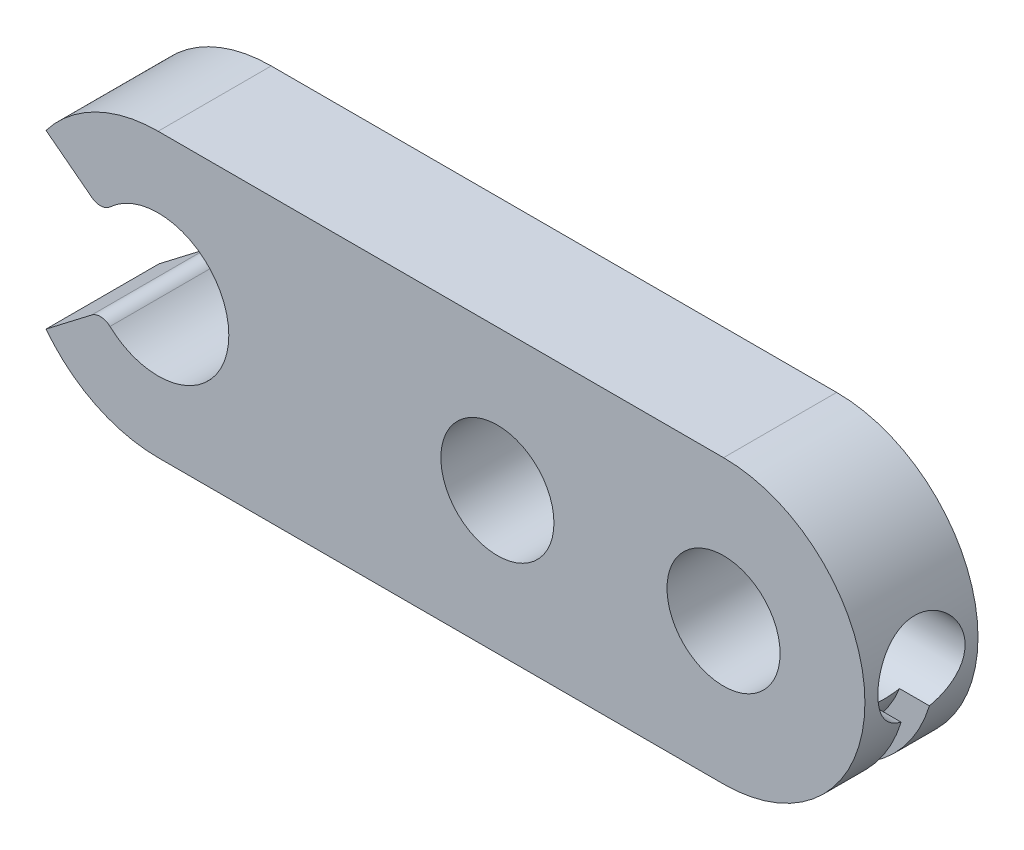
SolidWorks part; units mm, degrees
ref_plane "Front Plane" through (0, 0, 0) normal (0, 0, 1) x (1, 0, 0)
ref_plane "Top Plane" through (0, 0, 0) normal (0, 1, 0) x (1, 0, 0)
ref_plane "Right Plane" through (0, 0, 0) normal (1, 0, 0) x (0, 0, -1)
sketch "Sketch1" plane through (0, 0, 0) normal (0, 0, 1) x (1, 0, 0)
  line L0 (-3.9668, 3.0438) -> (-1.9834, 1.5219)
  line L1 (-1.9834, -1.5219) -> (-3.9668, -3.0438)
  line L2 (0, 5) -> (20, 5)
  line L3 (20, -5) -> (0, -5)
  arc A0 (-3.9668, 3.0438) -> (0, 5) centre (0, 0) cw
  arc A1 (-1.9834, 1.5219) -> (-1.9834, -1.5219) centre (0, 0) cw
  arc A2 (20, 5) -> (20, -5) centre (20, 0) cw
  arc A3 (0, -5) -> (-3.9668, -3.0438) centre (0, 0) cw
  dimension "D2" = 2.5
  dimension "D3" = 5
  dimension "D4" = 20
  dimension "D1" = 75
extrude "Boss-Extrude1" add sketch "Sketch1" along normal blind 4
fillet "Fillet1" radius 0.5 2 edges at (-1.9834, 1.5219, 2) (-1.9834, -1.5219, 2)
sketch "Sketch2" plane through (0, 0, 4) normal (0, 0, 1) x (1, 0, 0)
  circle A0 centre (20, 0) radius 2
  arc A1 (20, -5) -> (20, 5) centre (20, 0) ccw construction
  arc A2 (20, -5) -> (20, 5) centre (20, 0) ccw construction
  point P2 (20.0011, 2.2705)
  point P7 (15.4313, 0)
  point P8 (19.7712, 0)
  dimension "D1" = 4
extrude "Cut-Extrude1" cut sketch "Sketch2" against normal blind 10
sketch "Sketch3" plane through (0, 0, 4) normal (0, 0, 1) x (1, 0, 0)
  circle A2 centre (12, 0) radius 2
  point P2 (11.7761, 2.3074)
  point P3 (0, 0)
  dimension "D1" = 4
  dimension "D2" = 12
extrude "Cut-Extrude2" cut sketch "Sketch3" against normal up to vertex (4 mm away) up to point (0, 0, 0)
sketch "Sketch4" plane through (0, 0, 0) normal (1, 0, 0) x (0, 0, -1)
  line L0 (-2, 0) -> (-2, 5) construction
  line L1 (-4, 5) -> (0, 5) construction
  circle A0 centre (-2, 0) radius 1.5437
  dimension "D1" = 3.0875
extrude "Cut-Extrude3" cut sketch "Sketch4" against normal blind 30 from offset 50
sketch "Sketch5" plane through (0, 0, 0) normal (0, 0, -1) x (-1, 0, 0)
  line L19 (-24, 0) -> (-25, 0)
  line L20 (0, -4) -> (-20, -4)
  line L21 (3, -4) -> (-20, -4)
  line L23 (0, -5) -> (-20, -5)
  line L24 (0, -5) -> (-20, -5) construction
  line L25 (0, -5) -> (3, -5)
  line L30 (3, -5) -> (3, -4)
  arc A25 (-20, 5) -> (-20, -5) centre (-20, 0) ccw construction
  arc A26 (-20, 4) -> (-20, -4) centre (-20, 0) ccw
  arc A27 (-24, 0) -> (-20, -4) centre (-20, 0) ccw
  arc A28 (-20, -5) -> (-25, 0) centre (-20, 0) cw
  arc A29 (0, -5) -> (3.9668, -3.0438) centre (0, 0) ccw construction
  point P14 (0, 0)
  dimension "D1" = 1
ref_plane "Plane1" through (0, 0, 2) normal (0, 0, -1) x (-1, 0, 0)
extrude "Cut-Extrude4" cut sketch "Sketch5" against normal mid plane 1 from surface at -2 starting at plane "Plane1"
